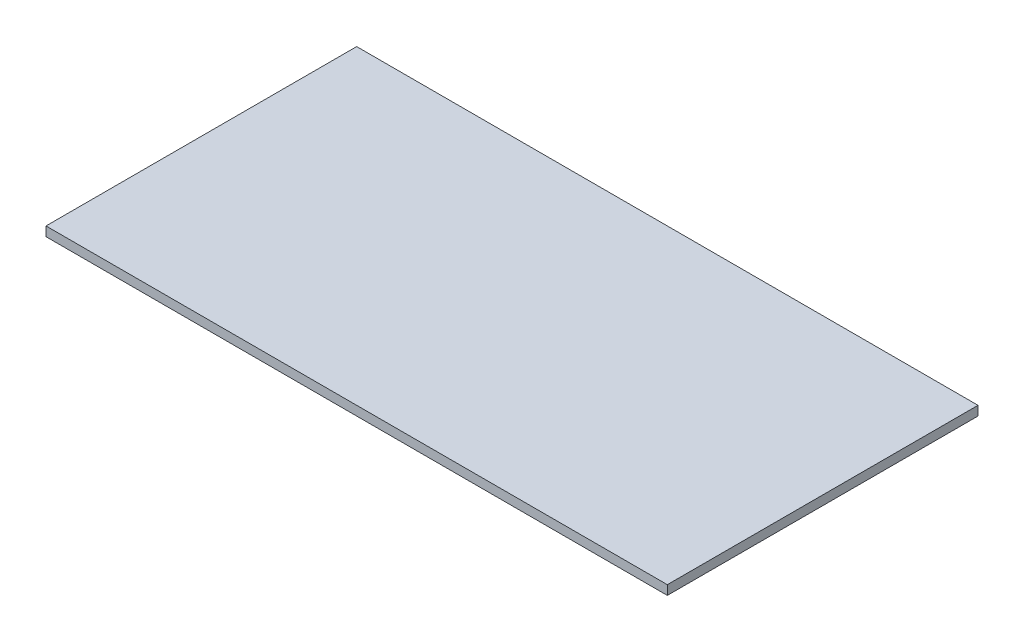
SolidWorks part; units mm, degrees
material "PE High Density"
ref_plane "Front Plane" through (0, 0, 0) normal (0, 0, 1) x (1, 0, 0)
ref_plane "Top Plane" through (0, 0, 0) normal (0, 1, 0) x (1, 0, 0)
ref_plane "Right Plane" through (0, 0, 0) normal (1, 0, 0) x (0, 0, -1)
sketch "Sketch1" plane through (0, 0, 0) normal (0, 1, 0) x (1, 0, 0)
  line L0 (-500, 250) -> (500, 250)
  line L1 (-500, 250) -> (-500, -250)
  line L2 (500, 250) -> (500, -250)
  line L3 (-500, -250) -> (500, -250)
  line L4 (-500, 250) -> (500, -250) construction
  line L5 (500, 250) -> (-500, -250) construction
  point P1 (0, 0)
  dimension "D1" = 1000
  dimension "D2" = 500
extrude "Boss-Extrude1" add sketch "Sketch1" along normal blind 15
